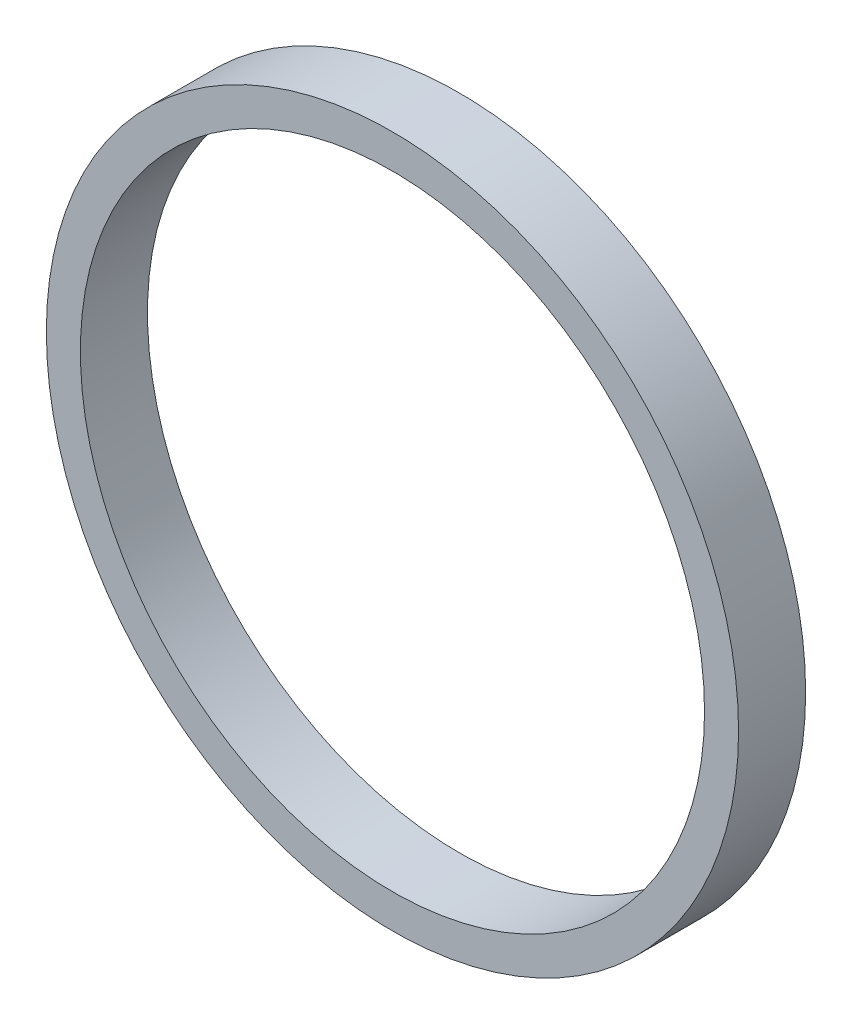
SolidWorks part; units mm, degrees
material "6061-T6 (SS)"
ref_plane "Front Plane" through (0, 0, 0) normal (0, 0, 1) x (1, 0, 0)
ref_plane "Top Plane" through (0, 0, 0) normal (0, 1, 0) x (1, 0, 0)
ref_plane "Right Plane" through (0, 0, 0) normal (1, 0, 0) x (0, 0, -1)
sketch "Sketch1" plane through (0, 0, 0) normal (1, 0, 0) x (0, 0, -1)
  line L0 (-35.627, 0) -> (36.4528, 0) construction
  line L1 (-2.6924, 25.05) -> (2.6924, 25.05)
  line L2 (-2.6924, 25.05) -> (-2.6924, 27.7812)
  line L3 (2.6924, 25.05) -> (2.6924, 27.7812)
  line L4 (-2.6924, 27.7812) -> (2.6924, 27.7812)
  line L5 (0, 0) -> (0, 25.05) construction
  dimension "D1" = 50.1
  dimension "D2" = 55.5625
  dimension "D3" = 5.3848
revolve "Revolve1" add sketch "Sketch1" angle 360 about L0
